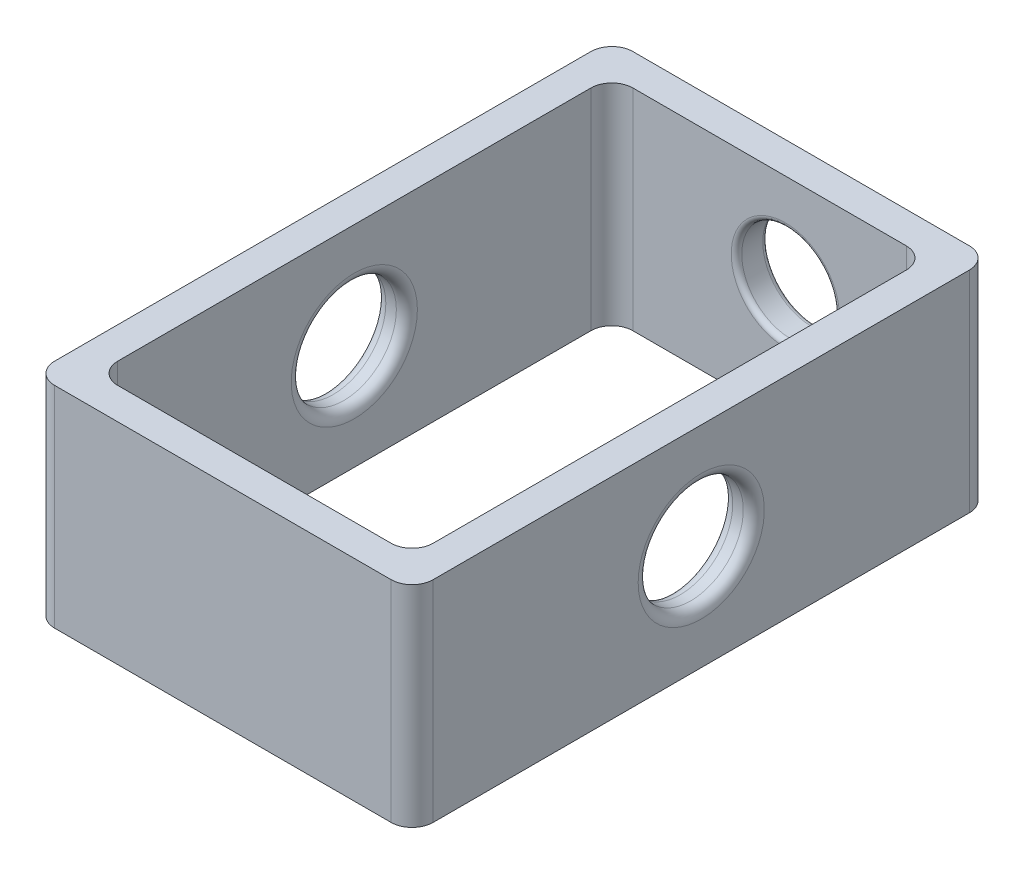
SolidWorks part; units mm, degrees
ref_plane "Plano frontal" through (0, 0, 0) normal (0, 0, 1) x (1, 0, 0)
ref_plane "Plano superior" through (0, 0, 0) normal (0, 1, 0) x (1, 0, 0)
ref_plane "Plano direito" through (0, 0, 0) normal (1, 0, 0) x (0, 0, -1)
sketch "Esboço1" plane through (0, 0, 0) normal (0, 1, 0) x (1, 0, 0)
  line L1 (-18, -27.5) -> (18, -27.5)
  line L2 (-18, -27.5) -> (-18, 27.5)
  line L3 (-18, 27.5) -> (18, 27.5)
  line L4 (18, -27.5) -> (18, 27.5)
  line L5 (-18, -27.5) -> (18, 27.5) construction
  line L6 (-18, 27.5) -> (18, -27.5) construction
  line L7 (15, -24.5) -> (-15, -24.5)
  line L8 (15, -24.5) -> (15, 24.5)
  line L9 (15, 24.5) -> (-15, 24.5)
  line L10 (-15, -24.5) -> (-15, 24.5)
  line L11 (15, -24.5) -> (-15, 24.5) construction
  line L12 (15, 24.5) -> (-15, -24.5) construction
  point P0 (0, 0)
  point P6 (0, 0)
  dimension "D1" = 36
  dimension "D2" = 55
  dimension "D3" = 3
  dimension "D4" = 3
extrude "Saliente-Extruir1" add sketch "Esboço1" along normal mid plane 20
sketch "Croquis8" plane through (-18, 0, 0) normal (-1, 0, 0) x (0, 0, 1)
  circle A0 centre (0, 0) radius 5
  dimension "D1" = 10
extrude "Cortar-Extruir4" cut sketch "Croquis8" against normal up to surface (36 mm away) up to face at (18, 0, 0)
fillet "Redondeo1" radius 2 4 edges at (18, 0, -27.5) (-18, 0, -27.5) (-18, 0, 27.5) (18, 0, 27.5)
fillet "Redondeo2" radius 2 4 edges at (15, 0, 24.5) (15, 0, -24.5) (-15, 0, -24.5) (-15, 0, 24.5)
sketch "Croquis9" plane through (0, 0, -27.5) normal (0, 0, -1) x (-1, 0, 0)
  line L0 (-16, 1) -> (-1.5, 1) construction
  line L1 (-16, 10) -> (16, 10) construction
  circle A0 centre (-1.5, 1) radius 4.65
  dimension "D3" = 9.3
  dimension "D1" = 9
  dimension "D2" = 14.5
extrude "Cortar-Extruir5" cut sketch "Croquis9" against normal blind 5 and the other way through all
fillet "Redondeo5" radius 0.5 2 edges at (6.15, 1, -24.5)
fillet "Redondeo6" radius 1 4 edges at (-18, 0, 5) (-15, 0, -5) (15, 0, 5) (18, 0, 5)
